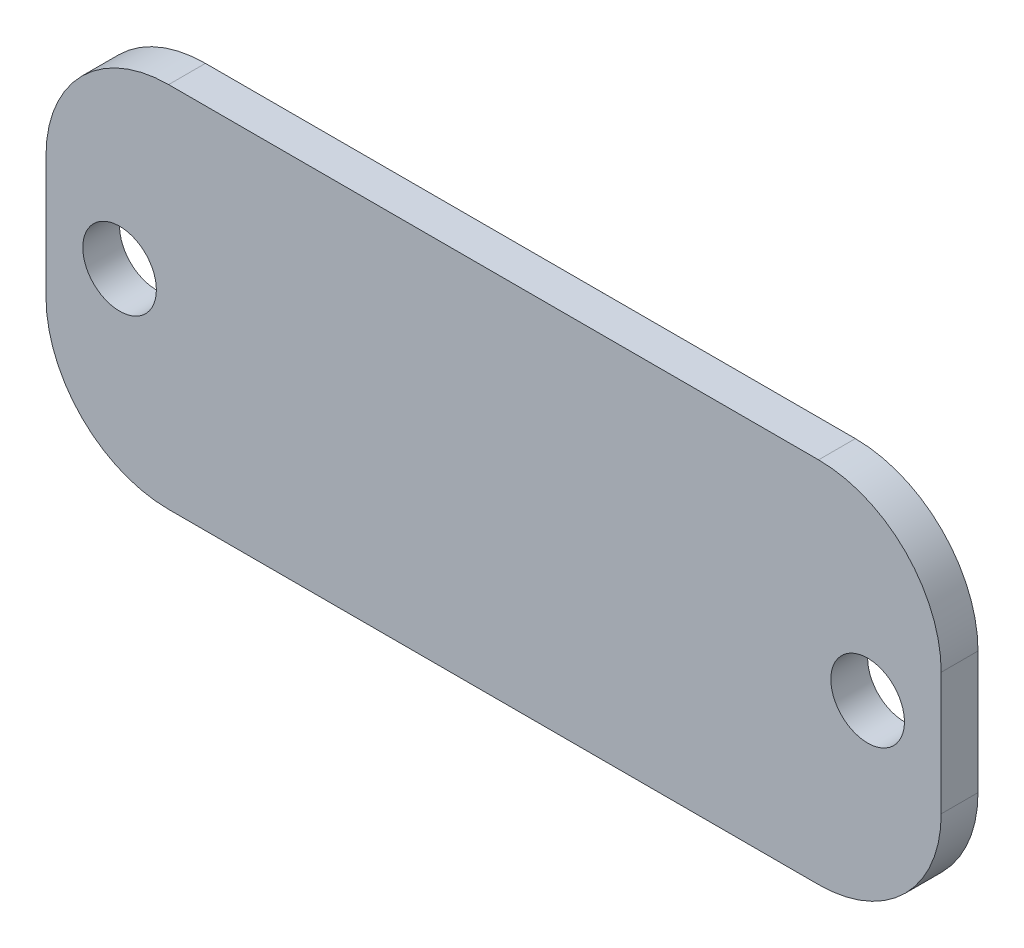
SolidWorks part; units mm, degrees
ref_plane "前视基准面" through (0, 0, 0) normal (0, 0, 1) x (1, 0, 0)
ref_plane "上视基准面" through (0, 0, 0) normal (0, 1, 0) x (1, 0, 0)
ref_plane "右视基准面" through (0, 0, 0) normal (1, 0, 0) x (0, 0, -1)
other "Configuration Table"
sketch "草图3" plane through (0, 0, 0) normal (0, 0, 1) x (1, 0, 0)
  line L0 (2.7618, 15) -> (62.7618, 15) construction
  line L1 (10, 0) -> (63, 0)
  line L2 (0, 10) -> (0, 20)
  line L3 (10, 30) -> (63, 30)
  line L4 (73, 10) -> (73, 20)
  circle A0 centre (6, 15) radius 3
  circle A2 centre (67, 15) radius 3
  arc A3 (63, 30) -> (73, 20) centre (63, 20) cw
  arc A4 (73, 10) -> (63, 0) centre (63, 10) cw
  arc A5 (10, 0) -> (0, 10) centre (10, 10) cw
  arc A6 (0, 20) -> (10, 30) centre (10, 20) cw
  point P17 (73, 0)
  point P20 (0, 0)
  point P23 (0, 30)
  dimension "D3" = 6
  dimension "D5" = 10
  dimension "D6" = 6
  dimension "D1" = 73
  dimension "D2" = 30
  dimension "D4" = 6
extrude "凸台-拉伸1" add sketch "草图3" along normal blind 3
